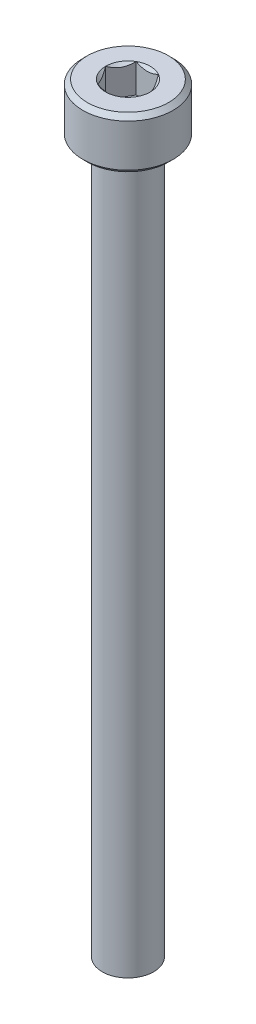
SolidWorks part; units mm, degrees
ref_plane "Front" through (0, 0, 0) normal (0, 0, 1) x (1, 0, 0)
ref_plane "Top" through (0, 0, 0) normal (0, 1, 0) x (1, 0, 0)
ref_plane "Right" through (0, 0, 0) normal (1, 0, 0) x (0, 0, -1)
sketch "Sketch1" plane through (0, 0, 0) normal (0, 1, 0) x (1, 0, 0)
  circle A0 centre (0, 0) radius 3.5
  dimension "D1" = 7
extrude "Boss-Extrude1" add sketch "Sketch1" along normal blind 4
sketch "Sketch2" plane through (0, 4, 0) normal (0, 1, 0) x (1, 0, 0)
  line L1 (0.866, 1.5) -> (-0.866, 1.5)
  line L2 (-0.866, 1.5) -> (-1.7321, 0)
  line L3 (-1.7321, 0) -> (-0.866, -1.5)
  line L4 (-0.866, -1.5) -> (0.866, -1.5)
  line L5 (0.866, -1.5) -> (1.7321, 0)
  line L6 (1.7321, 0) -> (0.866, 1.5)
  circle A0 centre (0, 0) radius 1.5 construction
  point P10 (0, 1.5)
  dimension "D1" = 3
extrude "Cut-Extrude1" cut sketch "Sketch2" against normal blind 2.25
sketch "Sketch3" plane through (0, 4, 0) normal (0, 1, 0) x (1, 0, 0)
  circle A0 centre (0, 0) radius 1.7321
extrude "Cut-Extrude2" cut sketch "Sketch3" against normal through all draft 45
chamfer "Chamfer1" distance 0.35 angle 45 2 edges at (0, 0, 3.5) (0, 4, 3.5)
sketch "草图1" plane through (0, 0, 0) normal (0, -1, 0) x (-1, 0, 0)
  circle A0 centre (0, 0) radius 2
  dimension "D1" = 4
extrude "凸台-拉伸1" add sketch "草图1" along normal blind 55
